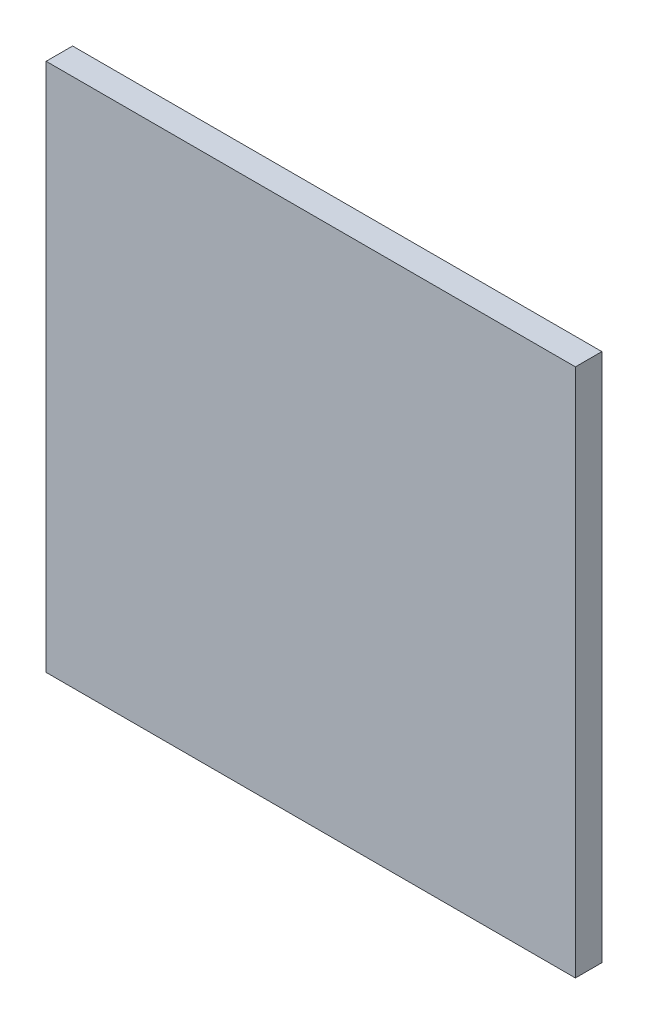
SolidWorks part; units mm, degrees
ref_plane "Front" through (0, 0, 0) normal (0, 0, 1) x (1, 0, 0)
ref_plane "Top" through (0, 0, 0) normal (0, 1, 0) x (1, 0, 0)
ref_plane "Right" through (0, 0, 0) normal (1, 0, 0) x (0, 0, -1)
sketch "Sketch1" plane through (0, 0, 0) normal (0, 0, 1) x (1, 0, 0)
  line L1 (-40, 40) -> (40, 40)
  line L2 (-40, 40) -> (-40, -40)
  line L3 (-40, -40) -> (40, -40)
  line L4 (40, 40) -> (40, -40)
  line L5 (-40, 40) -> (40, -40) construction
  line L6 (-40, -40) -> (40, 40) construction
  point P0 (0, 0)
  dimension "D1" = 80
  dimension "D2" = 80
extrude "Boss-Extrude1" add sketch "Sketch1" along normal blind 4
